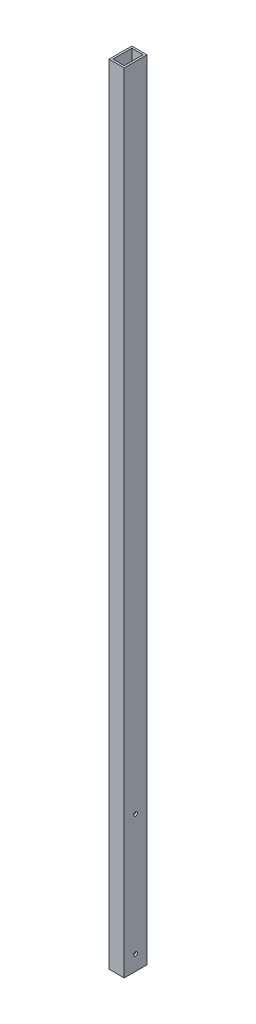
SolidWorks part; units mm, degrees
material "6061-T6 (SS)"
ref_plane "Front Plane" through (0, 0, 0) normal (0, 0, 1) x (1, 0, 0)
ref_plane "Top Plane" through (0, 0, 0) normal (0, 1, 0) x (1, 0, 0)
ref_plane "Right Plane" through (0, 0, 0) normal (1, 0, 0) x (0, 0, -1)
sketch "Sketch1" plane through (0, 0, 0) normal (0, 1, 0) x (1, 0, 0)
  line L1 (-12.7, -19.05) -> (12.7, -19.05)
  line L2 (-12.7, -19.05) -> (-12.7, 19.05)
  line L3 (-12.7, 19.05) -> (12.7, 19.05)
  line L4 (12.7, -19.05) -> (12.7, 19.05)
  line L5 (-12.7, -19.05) -> (12.7, 19.05) construction
  line L6 (-12.7, 19.05) -> (12.7, -19.05) construction
  line L7 (-9.525, -15.875) -> (9.525, -15.875)
  line L8 (-9.525, -15.875) -> (-9.525, 15.875)
  line L9 (-9.525, 15.875) -> (9.525, 15.875)
  line L10 (9.525, -15.875) -> (9.525, 15.875)
  line L11 (-9.525, -15.875) -> (9.525, 15.875) construction
  line L12 (-9.525, 15.875) -> (9.525, -15.875) construction
  point P0 (0, 0)
  point P5 (0, 0)
  dimension "D1" = 38.1
  dimension "D2" = 25.4
  dimension "D3" = 31.75
  dimension "D4" = 19.05
extrude "Boss-Extrude1" add sketch "Sketch1" along normal blind 1320.8
sketch "Sketch2" plane through (-12.7, 0, 0) normal (-1, 0, 0) x (0, 0, 1)
  line L0 (0, 0) -> (0, 25.4) construction
  line L1 (-19.05, 0) -> (19.05, 0) construction
  line L2 (0, 25.4) -> (0, 228.6) construction
  circle A0 centre (0, 25.4) radius 3.175
  circle A1 centre (0, 228.6) radius 3.175
  dimension "D3" = 6.35
  dimension "D1" = 203.2
  dimension "D2" = 25.4
extrude "Cut-Extrude1" cut sketch "Sketch2" against normal blind 3.175
mirror "Mirror1" about plane through (0, 0, 0) normal (1, 0, 0) of "Cut-Extrude1"
